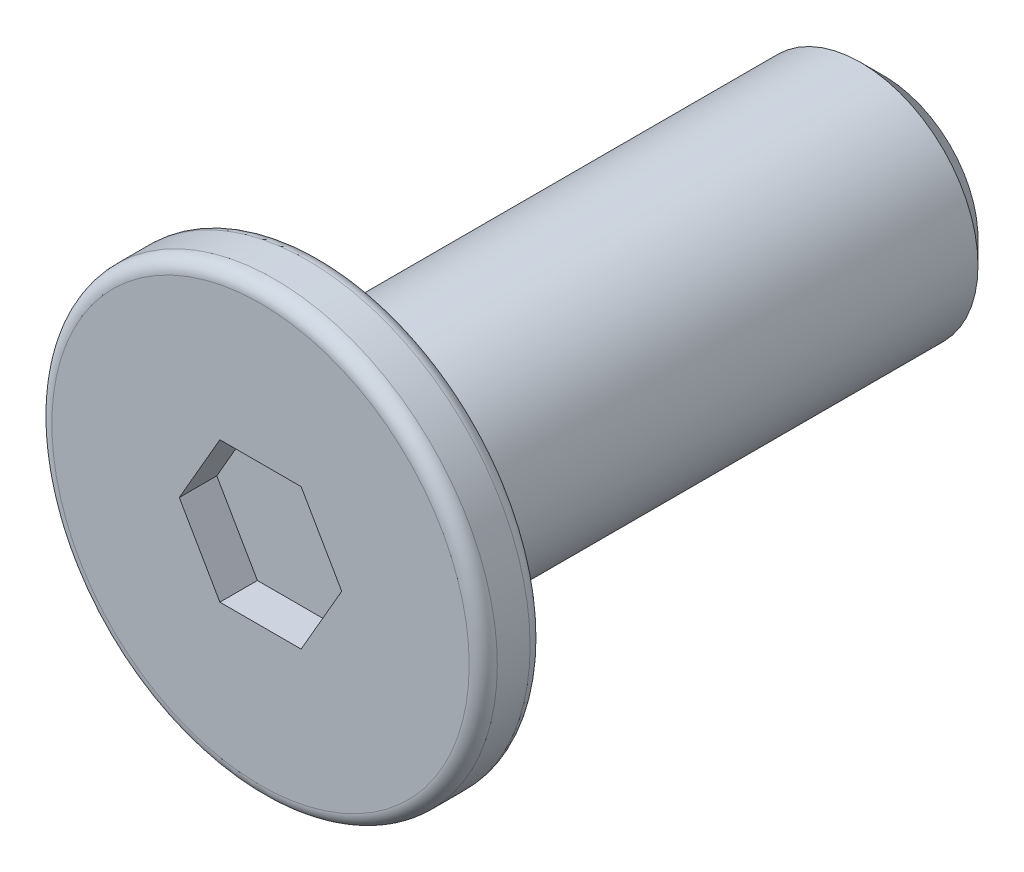
SolidWorks part; units mm, degrees
ref_plane "前视基准面" through (0, 0, 0) normal (0, 0, 1) x (1, 0, 0)
ref_plane "上视基准面" through (0, 0, 0) normal (0, 1, 0) x (1, 0, 0)
ref_plane "右视基准面" through (0, 0, 0) normal (1, 0, 0) x (0, 0, -1)
sketch "草图1" plane through (0, 0, 0) normal (0, 0, 1) x (1, 0, 0)
  circle A0 centre (0, 0) radius 4.75
  dimension "D1" = 9.5
extrude "凸台-拉伸1" add sketch "草图1" along normal mid plane 1.3
sketch "草图2" plane through (0, 0, -0.65) normal (0, 0, -1) x (-1, 0, 0)
  circle A0 centre (0, 0) radius 2.5
  dimension "D1" = 5
extrude "凸台-拉伸2" add sketch "草图2" along normal blind 12
chamfer "倒角1" distance 0.5 angle 45 1 edges at (-2.5, 0, -12.65)
sketch "草图3" plane through (0, 0, 0.65) normal (0, 0, 1) x (1, 0, 0)
  line L1 (1.7321, 0) -> (0.866, 1.5)
  line L2 (0.866, 1.5) -> (-0.866, 1.5)
  line L3 (-0.866, 1.5) -> (-1.7321, 0)
  line L4 (-1.7321, 0) -> (-0.866, -1.5)
  line L5 (-0.866, -1.5) -> (0.866, -1.5)
  line L6 (0.866, -1.5) -> (1.7321, 0)
  circle A0 centre (0, 0) radius 1.5 construction
  dimension "D1" = 3
extrude "切除-拉伸1" cut sketch "草图3" against normal blind 0.8
fillet "圆角2" radius 0.3 2 edges at (4.75, 0, -0.65) (4.75, 0, 0.65)
